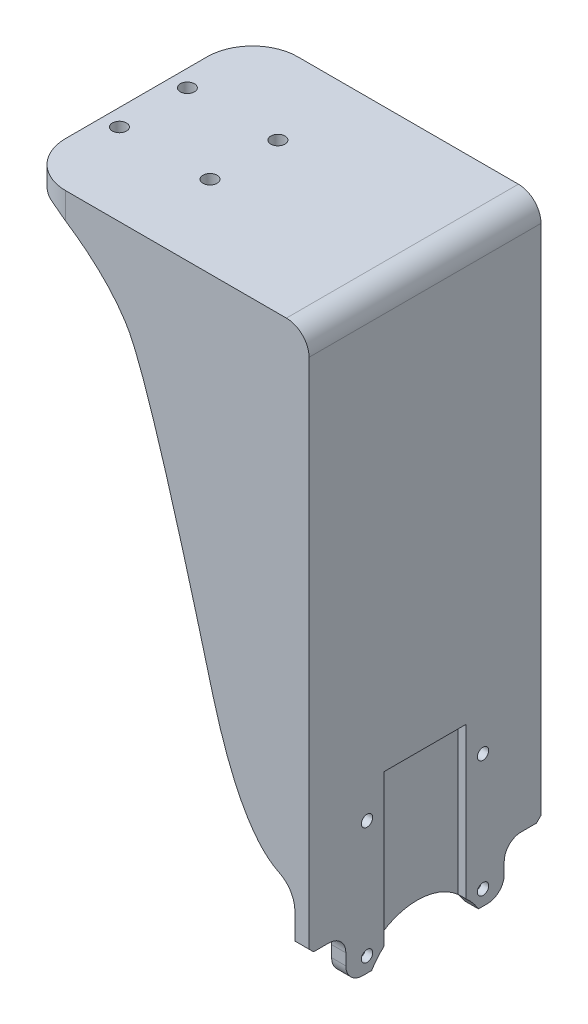
SolidWorks part; units mm, degrees
ref_plane "前视基准面" through (0, 0, 0) normal (0, 0, 1) x (1, 0, 0)
ref_plane "上视基准面" through (0, 0, 0) normal (0, 1, 0) x (1, 0, 0)
ref_plane "右视基准面" through (0, 0, 0) normal (1, 0, 0) x (0, 0, -1)
other "Configuration Table"
sketch "草图1" plane through (0, 0, 0) normal (0, 1, 0) x (1, 0, 0)
  line L0 (-22.5, 11.2328) -> (-22.5, -19.6928) construction
  line L1 (-25.5, 20.5) -> (25.5, 20.5)
  line L2 (-25.5, 20.5) -> (-25.5, -20.5)
  line L3 (-25.5, -20.5) -> (25.5, -20.5)
  line L4 (25.5, 20.5) -> (25.5, -20.5)
  line L5 (-25.5, 20.5) -> (25.5, -20.5) construction
  line L6 (-25.5, -20.5) -> (25.5, 20.5) construction
  line L7 (-17.7344, 0) -> (22.5332, 0) construction
  circle A0 centre (-22.5, 6) radius 1.25
  circle A1 centre (-22.5, -6) radius 1.25
  circle A2 centre (-6.5, 6) radius 1.25
  circle A3 centre (-6.5, -6) radius 1.25
  point P0 (0, 0)
  dimension "D3" = 2.5
  dimension "D4" = 12
  dimension "D6" = 16
  dimension "D7" = 2.5
  dimension "D1" = 41
  dimension "D2" = 3
  dimension "D5" = 51
extrude "凸台-拉伸1" add sketch "草图1" along normal blind 3.4
sketch "草图2" plane through (25.5, 0, 0) normal (1, 0, 0) x (0, 0, -1)
  line L0 (-20.5, 0) -> (20.5, 0)
  line L1 (20.5, 0) -> (20.5, -100)
  line L2 (20.5, -100) -> (9.4381, -100)
  line L3 (-20.5, -100) -> (-20.5, 0)
  line L4 (0, 12.0877) -> (0, -94.65) construction
  line L5 (-30.0581, -87) -> (27.3842, -87) construction
  line L6 (-9.4381, -100) -> (-20.5, -100)
  line L7 (0, -64) -> (0, -84.8169) construction
  circle A0 centre (-10.25, -97.35) radius 1
  circle A1 centre (10.25, -97.35) radius 1
  circle A2 centre (10.25, -76.65) radius 1
  circle A3 centre (-10.25, -76.65) radius 1
  arc A4 (9.4381, -100) -> (-9.4381, -100) centre (0, -105.65) ccw
  dimension "D3" = 2
  dimension "D4" = 20.5
  dimension "D5" = 20.7
  dimension "D6" = 8.3
  dimension "D7" = 11
  dimension "D1" = 100
  dimension "D2" = 13
extrude "凸台-拉伸2" add sketch "草图2" against normal blind 2.5
sketch "草图3" plane through (25.5, 0, 0) normal (1, 0, 0) x (0, 0, -1)
  line L0 (0, 9.7576) -> (0, -76.6891) construction
  line L5 (-7.25, -70.65) -> (-7.25, -106.3874)
  line L6 (-7.25, -106.3874) -> (7.25, -106.3874)
  line L7 (-7.25, -70.65) -> (7.25, -70.65)
  line L8 (7.25, -70.65) -> (7.25, -106.3874)
  circle A0 centre (-10.25, -76.65) radius 1 construction
  point P10 (0, -70.65)
  point P11 (0, -106.3874)
  dimension "D2" = 6
  dimension "D1" = 3
extrude "切除-拉伸1" cut sketch "草图3" against normal blind 1.4
sketch "草图5" plane through (0, 0, -20.5) normal (0, 0, -1) x (-1, 0, 0)
  line L0 (-25.5, 3.4) -> (19.5, 3.4)
  line L1 (-25.5, -82.805) -> (-25.5, 3.4)
  line L2 (19.5, 3.4) -> (19.5, 0)
  line L3 (-25.5, -82.805) -> (-23, -82.805)
  line L5 (-25.5, 3.4) -> (-25.5, -100) construction
  line L6 (25.5, 3.4) -> (25.5, 0) construction
  spline S0 degree 2 poles (19.5, 0) (10.6712, -5.3693) (2.7794, -18.1934) (-14.2375, -82.4755) (-23, -82.805) knots 0 0 0 0.396049 0.78858 1 1 1
  point P7 (-25.5, 3.4)
  dimension "D1" = 6
extrude "凸台-拉伸4" add sketch "草图5" against normal blind 2
mirror "镜向3" about plane through (0, 0, 0) normal (0, 0, 1) of "凸台-拉伸4"
fillet "圆角1" radius 8 2 edges at (-25.5, 1.7, -20.5) (-25.5, 1.7, 20.5)
fillet "圆角2" radius 4 2 edges at (23, 0, 0) (25.5, 3.4, 0)
sketch "草图6" plane through (23, 0, 0) normal (-1, 0, 0) x (0, 0, 1)
  circle A0 centre (10.25, -97.35) radius 2
  circle A1 centre (-10.25, -97.35) radius 2
  dimension "D1" = 4
  dimension "D2" = 4
extrude "切除-拉伸2" cut sketch "草图6" against normal blind 1.2
sketch "草图8" plane through (25.5, 0, 0) normal (1, 0, 0) x (0, 0, -1)
  line L0 (14, -102.818) -> (14, -92)
  line L1 (14, -92) -> (23.4685, -92)
  line L2 (23.4685, -92) -> (23.4685, -110.0082)
  line L3 (23.4685, -110.0082) -> (-23.4685, -110.0082)
  line L4 (-23.4685, -92) -> (-23.4685, -110.0082)
  line L5 (0, -27.3846) -> (0, -80.1854) construction
  line L6 (-14, -92) -> (-23.4685, -92)
  line L7 (-14, -102.818) -> (-14, -92)
  line L8 (-14, -102.818) -> (14, -102.818)
  line L9 (9.4381, -100) -> (20.5, -100) construction
  point P9 (0, -110.0082)
  dimension "D1" = 28
  dimension "D2" = 8
extrude "切除-拉伸3" cut sketch "草图8" against normal blind 4
fillet "圆角3" radius 3 4 edges at (24.25, -100, -14) (24.25, -92, -14) (24.25, -92, 14) (24.25, -100, 14)
sketch "草图9" plane through (23, 0, 0) normal (-1, 0, 0) x (0, 0, 1)
  line L0 (0, 14.9311) -> (0, -25.9548) construction
  circle A0 centre (10.25, -76.65) radius 2
  circle A1 centre (-10.25, -76.65) radius 2
  dimension "D1" = 4
extrude "切除-拉伸4" cut sketch "草图9" against normal blind 0.8
sketch "草图10" plane through (0, 0, 0) normal (0, -1, 0) x (-1, 0, 0)
  line L0 (28.9726, 0) -> (-5.0372, 0) construction
  line L1 (6.5, -6) -> (22.5, -6) construction
  line L2 (14.5, -8.9106) -> (14.5, 10.615) construction
  circle A0 centre (6.5, -6) radius 2.5
  circle A2 centre (22.5, -6) radius 2.5
  circle A3 centre (6.5, 6) radius 2.5
  circle A4 centre (22.5, 6) radius 2.5
  dimension "D1" = 5
extrude "切除-拉伸5" cut sketch "草图10" against normal blind 1.4
chamfer "倒角1" distance 0.8 angle 45 2 edges at (24.25, -92, 20.5) (24.25, -92, -20.5)
fillet "圆角4" radius 4 6 edges at (-0.25, 0, -18.5) (21.8284, -1.1716, -18.5) (-0.25, 0, 18.5) (21.8284, -1.1716, 18.5) (23, -43.4025, -18.5) (23, -43.4025, 18.5)
fillet "圆角5" radius 5 4 edges at (23, -82.805, 17.5) (23, -82.805, -17.5) (-19.5, 0, 17.373) (-19.5, 0, -17.373)
